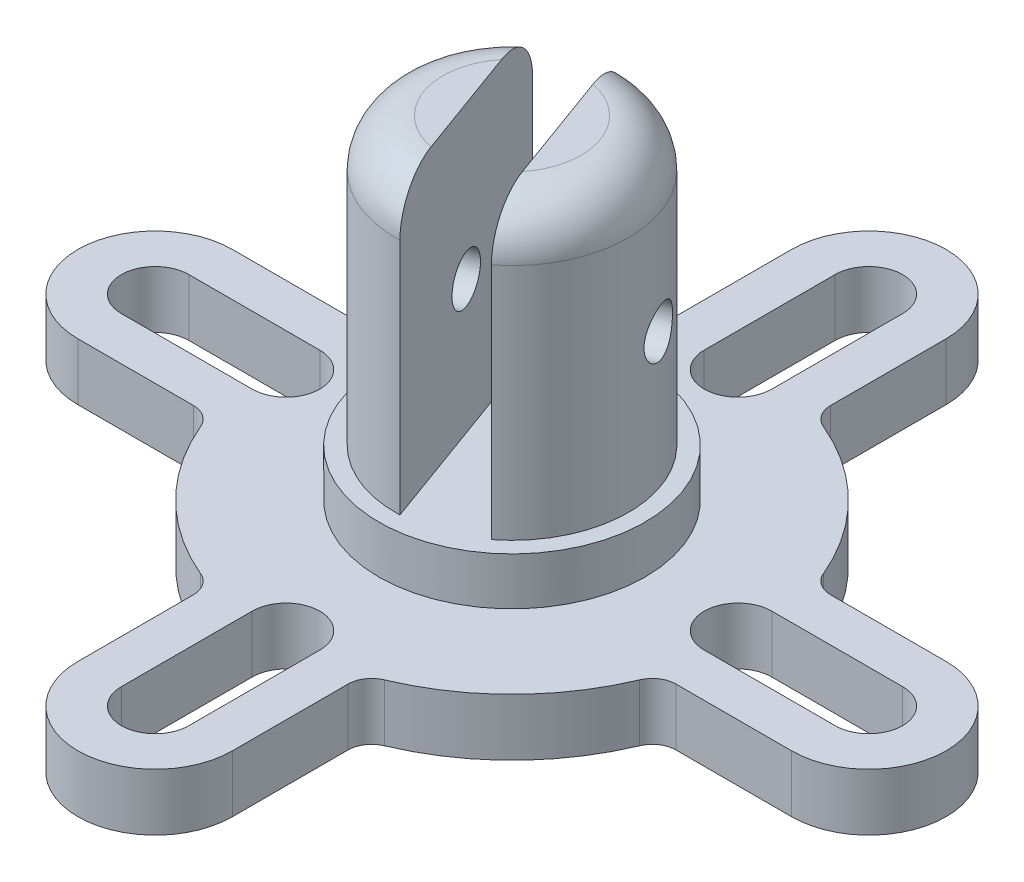
SolidWorks part; units mm, degrees
material "GPS İSKELET"
ref_plane "Ön Düzlem" through (0, 0, 0) normal (0, 0, 1) x (1, 0, 0)
ref_plane "Üst Düzlem" through (0, 0, 0) normal (0, 1, 0) x (1, 0, 0)
ref_plane "Sağ Düzlem" through (0, 0, 0) normal (1, 0, 0) x (0, 0, -1)
sketch "Sketch1" plane through (0, 0, 0) normal (0, 1, 0) x (1, 0, 0)
  line L0 (-340.0605, 0) -> (16662.9662, 0) construction
  line L1 (0, -340.0605) -> (0, 16662.9662) construction
  line L2 (-15, 3.25) -> (-9.4571, 3.25)
  line L3 (-15, -3.25) -> (-9.4571, -3.25)
  line L4 (-15, 0) -> (-9.5, 0) construction
  line L5 (-15, 1.42) -> (-9.5, 1.42)
  line L6 (-15, -1.42) -> (-9.5, -1.42)
  line L7 (3.25, 15) -> (3.25, 9.4571)
  line L8 (-3.25, 15) -> (-3.25, 9.4571)
  line L9 (0, 15) -> (0, 9.5) construction
  line L10 (1.42, 15) -> (1.42, 9.5)
  line L11 (-1.42, 15) -> (-1.42, 9.5)
  line L12 (15, -3.25) -> (9.4571, -3.25)
  line L13 (15, 3.25) -> (9.4571, 3.25)
  line L14 (15, 0) -> (9.5, 0) construction
  line L15 (15, -1.42) -> (9.5, -1.42)
  line L16 (15, 1.42) -> (9.5, 1.42)
  line L17 (-3.25, -15) -> (-3.25, -9.4571)
  line L18 (3.25, -15) -> (3.25, -9.4571)
  line L19 (0, -15) -> (0, -9.5) construction
  line L20 (-1.42, -15) -> (-1.42, -9.5)
  line L21 (1.42, -15) -> (1.42, -9.5)
  arc A0 (-15, 3.25) -> (-15, -3.25) centre (-15, 0) ccw
  arc A1 (-9.4571, -3.25) -> (-3.25, -9.4571) centre (0, 0) ccw
  arc A2 (-15, 1.42) -> (-15, -1.42) centre (-15, 0) ccw
  arc A3 (-9.5, -1.42) -> (-9.5, 1.42) centre (-9.5, 0) ccw
  arc A4 (3.25, 15) -> (-3.25, 15) centre (0, 15) ccw
  arc A5 (1.42, 15) -> (-1.42, 15) centre (0, 15) ccw
  arc A6 (-1.42, 9.5) -> (1.42, 9.5) centre (0, 9.5) ccw
  arc A7 (15, -3.25) -> (15, 3.25) centre (15, 0) ccw
  arc A8 (15, -1.42) -> (15, 1.42) centre (15, 0) ccw
  arc A9 (9.5, 1.42) -> (9.5, -1.42) centre (9.5, 0) ccw
  arc A10 (-3.25, -15) -> (3.25, -15) centre (0, -15) ccw
  arc A11 (-1.42, -15) -> (1.42, -15) centre (0, -15) ccw
  arc A12 (1.42, -9.5) -> (-1.42, -9.5) centre (0, -9.5) ccw
  arc A13 (-3.25, 9.4571) -> (-9.4571, 3.25) centre (0, 0) ccw
  arc A15 (9.4571, 3.25) -> (3.25, 9.4571) centre (0, 0) ccw
  arc A17 (3.25, -9.4571) -> (9.4571, -3.25) centre (0, 0) ccw
  point P6 (-12.25, 0)
  point P21 (0, 12.25)
  point P32 (12.25, 0)
  point P43 (0, -12.25)
  dimension "D1" = 6.5
  dimension "D3" = 20
  dimension "D4" = 1.42
  dimension "D2" = 15
  dimension "D5" = 5.5
  dimension "D6" = 4
extrude "Boss-Extrude1" add sketch "Sketch1" along normal blind 2.4
fillet "Fillet1" radius 1 8 edges at (9.4571, 1.2, -3.25) (3.25, 1.2, -9.4571) (-3.25, 1.2, -9.4571) (-9.4571, 1.2, -3.25) (-9.4571, 1.2, 3.25) (-3.25, 1.2, 9.4571) (9.4571, 1.2, 3.25) (3.25, 1.2, 9.4571)
sketch "Sketch2" plane through (0, 0, 0) normal (0, 0, 1) x (1, 0, 0)
  line L0 (0, 4.4) -> (0, 16.4)
  line L1 (3.25, 2.4) -> (-3.25, 2.4) construction
  line L2 (3.25, 2.4) -> (-3.25, 2.4)
  line L4 (0, 2.4) -> (5.6, 2.4)
  line L5 (0, 2.4) -> (0, 4.4)
  line L6 (4.9, 4.4) -> (5.6, 4.4)
  line L7 (5.6, 2.4) -> (5.6, 4.4)
  line L10 (0, 16.4) -> (2.9, 16.4)
  line L11 (4.9, 4.4) -> (4.9, 14.4)
  arc A0 (2.9, 16.4) -> (4.9, 14.4) centre (2.9, 14.4) cw
  point P5 (0, 2.4)
  dimension "D5" = 2
  dimension "D1" = 5.6
  dimension "D2" = 2
  dimension "D3" = 14
  dimension "D4" = 0.7
  dimension "D6" = 4.9
revolve "Revolve2" add sketch "Sketch2" angle 360 about L0
sketch "Sketch5" plane through (0, 16.4, 0) normal (0, 1, 0) x (1, 0, 0)
  line L0 (0, 0) -> (-7.0711, 7.0711) construction
  line L7 (0, 0) -> (-3.9977, 10.9837) construction
  line L8 (0, 0) -> (10.7314, 3.9059) construction
  line L9 (3.005, -3.8704) -> (-0.1859, 4.8965)
  line L10 (0.1859, -4.8965) -> (-3.005, 3.8704)
  arc A0 (-3.8636, 9.2235) -> (-9.2235, 3.8636) centre (0, 0) ccw construction
  circle A1 centre (0, 0) radius 4.9 construction
  arc A2 (-0.1859, 4.8965) -> (-3.4648, 3.4648) centre (0, 0) ccw
  arc A3 (0.1859, -4.8965) -> (3.005, -3.8704) centre (0, 0) ccw
  point P15 (1.4095, 0.513)
  point P16 (-1.4095, -0.513)
  circle M6 centre (0, 0) radius 2.9
  dimension "D1" = 90
  dimension "D2" = 25
  dimension "D3" = 3
extrude "Cut-Extrude1" cut sketch "Sketch5" against normal up to surface (12 mm away) contours L10 L9 M6 | L10 A3 L9 M6 | L9 A2 L10 M6 up to face at (0, 4.4, -5.6)
sketch "Sketch6" plane through (1.4095, 0, -0.513) normal (-0.9397, 0, 0.342) x (0.342, 0, 0.9397)
  line L0 (0, 16.4) -> (0, 4.4) construction
  line L1 (2.4819, 16.4) -> (-2.4819, 16.4) construction
  line L2 (5.6, 4.4) -> (-5.6, 4.4) construction
  line L3 (-2.0763, 2.4) -> (-8.3803, 2.4) construction
  circle A0 centre (0, 10) radius 1
  dimension "D1" = 2
  dimension "D2" = 6.4
  dimension "D3" = 7.6
extrude "Cut-Extrude2" cut sketch "Sketch6" against normal through all and the other way through all
